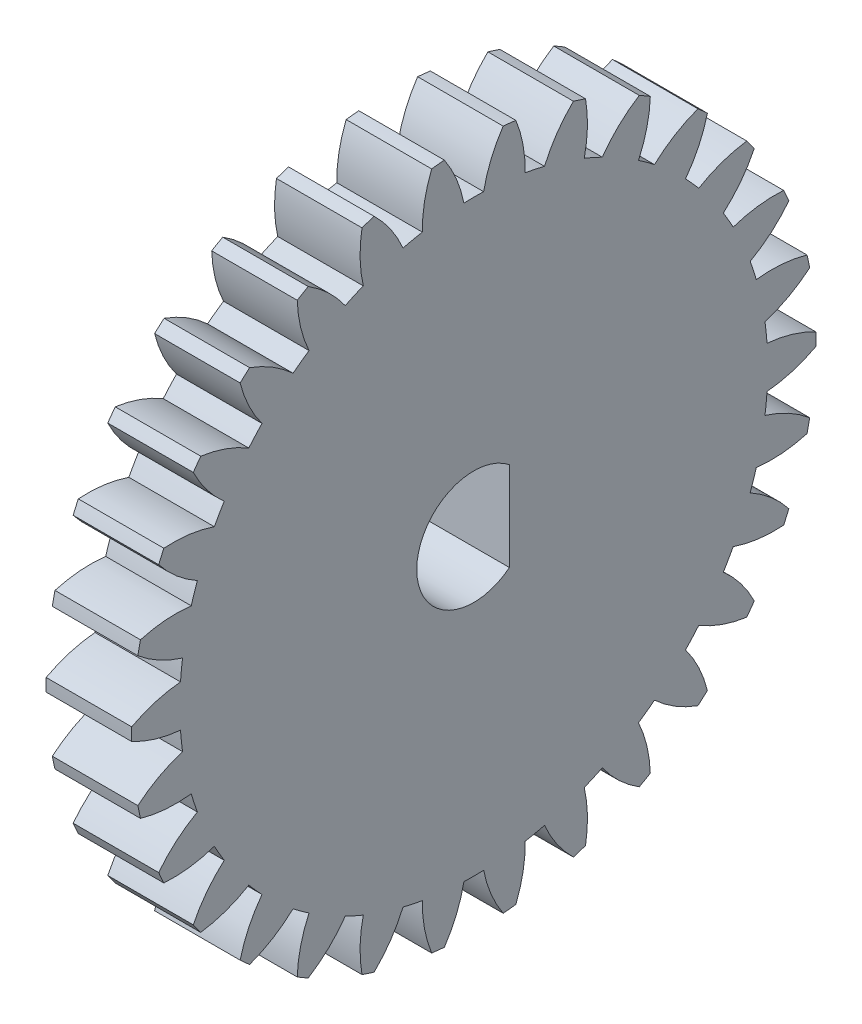
SolidWorks part; units mm, degrees
ref_plane "Plane1" through (0, 0, 0) normal (0, 0, 1) x (1, 0, 0)
ref_plane "Plane2" through (0, 0, 0) normal (0, 1, 0) x (1, 0, 0)
ref_plane "Plane3" through (0, 0, 0) normal (1, 0, 0) x (0, 0, -1)
sketch "HoldingSke" plane through (0, 0, 0) normal (0, 1, 0) x (1, 0, 0)
  line L0 (0, 0) -> (0.5774, -0.3333)
  line L1 (-15, 0) -> (100, 0) construction
  line L2 (0, 0) -> (-2.1039, 2.3779)
  line L3 (0, 0) -> (-11.863, 4.5341)
  line L4 (0, 0) -> (7.479, 4.318)
  line L5 (0, 0) -> (-46.8476, -17.4728)
  line L6 (0, 0) -> (-9.9476, -6.7116)
  line L7 (-2.1039, 2.3779) -> (8.6586, 51.2059)
  line L8 (-76.2, 54.61) -> (-76.1, 54.61)
  line L9 (-71.009, 38.7566) -> (-53.1078, 45.2721)
  line L10 (-76.2, 71.12) -> (104.1128, 71.12)
  line L11 (0, 0) -> (-12, 0)
  line L12 (-76.2, 101.6) -> (-76.147, 101.6)
  line L13 (24.9733, 27.94) -> (52.9518, 28.4284)
  line L14 (24.9733, 27.94) -> (24.9743, 27.94)
  line L15 (24.9733, 27.94) -> (100.4006, 29.5858)
  line L16 (-63.627, -1.5) -> (-12.827, -1.5)
  circle A0 centre (0, 0) radius 0.4
  circle A1 centre (0, 0) radius 20.624
  circle A2 centre (0, 0) radius 37.5
  circle A3 centre (0, 0) radius 0.4
  dimension "MHD" = 41.248
  dimension "Hub_dia" = 75
  dimension "Bore" = 0.8
  dimension "MBD" = 0.8
  dimension "Num_teeth" = 30
  dimension "Pitch_radius" = 180.3128
  dimension "Pitch" = 0.6667
  dimension "Width" = 12
  dimension "Overall_len" = 50
  dimension "Show_teeth" = 30
  dimension "Thickness" = 12
  dimension "OAL" = 50.0001
  dimension "T_dim" = 0.1
  dimension "Ap" = 20
  dimension "H" = 19.05
  dimension "Backlash" = 0.053
  dimension "Addendum_fac" = 1
  dimension "Dedendum_fac" = 1.25
  dimension "Clearance_fac" = 0.25
  dimension "Dedendum_add" = 0.001
  dimension "Module" = 1.5
sketch "BasProSke" plane through (0, 0, 0) normal (0, 1, 0) x (1, 0, 0)
  line L0 (-10, 0) -> (60, 0) construction
  line L1 (0, 0) -> (0, 24)
  line L2 (0, 0) -> (12, 0)
  line L3 (12, 0) -> (12, 24)
  line L4 (12, 24) -> (0, 24)
  dimension "Diameter" = 48
  dimension "Thickness" = 12
revolve "Base-Revolve" add sketch "BasProSke" angle 360 about L0
sketch "TooCutSke" plane through (0, 0, 0) normal (1, 0, 0) x (0, 0, -1)
  line L1 (0, 0) -> (0, 107) construction
  line L2 (0, 0) -> (-1.2703, 22.4641) construction
  line L3 (0, 0) -> (-4.6983, 44.7014) construction
  line L4 (-1.2703, 22.4641) -> (-2.3492, 22.3507) construction
  arc A0 (0.6933, 20.6123) -> (-0.6933, 20.6123) centre (0, 0) ccw
  arc A1 (2.0805, 23.9351) -> (-2.0805, 23.9351) centre (0, 0) ccw
  circle A2 centre (0, 0) radius 22.5 construction
  circle A3 centre (0, 0) radius 21.1431 construction
  arc A4 (-0.6933, 20.6123) -> (-2.0805, 23.9351) centre (-9.5243, 18.8764) ccw
  arc A5 (2.0805, 23.9351) -> (0.6933, 20.6123) centre (9.5243, 18.8764) ccw
  dimension "Root_dia" = 41.248
  dimension "Overcut_dia" = 48.0508
  dimension "Pitch_dia" = 45
  dimension "Base_dia" = 42.2862
  dimension "Flank_rad" = 9
  dimension "Half_ang" = 6
  dimension "Half_CT" = 1.0848
extrude "ToothCut" cut sketch "TooCutSke" along normal through all
fillet "Breaks" [suppressed] radius 0.03
fillet "RootFillets" [suppressed] radius 0.376
pattern_circular "TeethCuts" count 30 every 12 about axis through (-10, 0, 0) along (1, 0, 0) of "ToothCut", "RootFillets", "Breaks"
sketch "HubNeaOneSke" plane through (0, 0, 0) normal (-1, 0, 0) x (0, 0, 1)
  circle A0 centre (0, 0) radius 20.624
  dimension "Diameter" = 41.248
extrude "HubNearOne" [suppressed] add sketch "HubNeaOneSke" along normal blind 38.0001
sketch "HubNeaBotSke" plane through (0, 0, 0) normal (-1, 0, 0) x (0, 0, 1)
  circle A0 centre (0, 0) radius 20.624
  dimension "Diameter" = 41.248
extrude "HubNearBoth" [suppressed] add sketch "HubNeaBotSke" along normal blind 19
ref_plane "FarPln" through (12, 0, 0) normal (1, 0, 0) x (0, 0, -1)
sketch "HubFarSke" plane through (12, 0, 0) normal (1, 0, 0) x (0, 0, -1)
  circle A0 centre (0, 0) radius 20.624
  dimension "Diameter" = 41.248
extrude "HubFar" [suppressed] add sketch "HubFarSke" along normal blind 19
sketch "BorSke" plane through (0, 0, 0) normal (1, 0, 0) x (0, 0, -1)
  circle A0 centre (0, 0) radius 0.4
  dimension "Diameter" = 0.8
extrude "Bore" cut sketch "BorSke" along normal mid plane 100.0001
sketch "KeySke" plane through (0, 0, 0) normal (1, 0, 0) x (0, 0, -1)
  line L0 (-0.05, 0) -> (-0.05, 0.5)
  line L1 (-0.05, 0.5) -> (0.05, 0.5)
  line L2 (0.05, 0.5) -> (0.05, 0)
  line L3 (0, 0) -> (0, 34) construction
  line L4 (-0.05, 0) -> (0.05, 0)
  dimension "Offset" = 0.5
  dimension "Width" = 0.1
extrude "Keyway" [suppressed] cut sketch "KeySke" along normal mid plane 100.0001
pattern_circular "Keyway2" [suppressed] count 2 every 90 about axis through (-10, 0, 0) along (1, 0, 0)
sketch "Sketch1" plane through (0, 0, 0) normal (-1, 0, 0) x (0, 0, 1)
  circle A0 centre (-0.4, 0) radius 33.8416
  circle A1 centre (0, 0) radius 0.4 construction
extrude "Cut-Extrude1" cut sketch "Sketch1" against normal offset from surface (6 mm away) 6 up to face at (12, 0, 0)
sketch "Sketch2" plane through (6, 0, 0) normal (-1, 0, 0) x (0, 0, 1)
  line L0 (-2.5, 3.1225) -> (-2.5, -3.1225)
  circle A0 centre (0, 0) radius 4
  dimension "D1" = 8
  dimension "D2" = 2.5
extrude "Cut-Extrude2" cut sketch "Sketch2" against normal blind 6 contours L0 A0
equation "' \"Module@HoldingSke\" = 6.35"
equation "' \"Num_teeth@HoldingSke\" = 12"
equation "' \"Ap@HoldingSke\" =  20"
equation "' \"Width@HoldingSke\" = 0.5 * 25.4"
equation "' \"Hub_dia@HoldingSke\"= 1 * 25.4"
equation "' \"Overall_len@HoldingSke\" = 1.0 * 25.4"
equation "' \"Bore@HoldingSke\" = 0.75 * 25.4"
equation "' \"T_dim@HoldingSke\" = 0.1 * 25.4"
equation "' \"Width@KeySke\" = 0.25 * 25.4"
equation "' \"Show_teeth@HoldingSke\" = 13"
equation "' \"Backlash@HoldingSke\" = 0.009 * 25.4"
equation "' \"Addendum_fac@HoldingSke\" = 1.0"
equation "' \"Dedendum_fac@HoldingSke\" = 1.25"
equation "' \"Dedendum_add@HoldingSke\" = 0.00005 * 25.4"
equation "' \"Clearance_fac@HoldingSke\" = 0.25"
equation "\"Pitch@HoldingSke\" = 1 / \"Module@HoldingSke\""
equation "\"Overcut_dia@TooCutSke\" = (\"Num_teeth@HoldingSke\" + 2 * \"Addendum_fac@HoldingSke\") / \"Pitch@HoldingSke\" + 0.002 * 25.4"
equation "\"Pitch_dia@TooCutSke\" = \"Num_teeth@HoldingSke\" / \"Pitch@HoldingSke\""
equation "\"Base_dia@TooCutSke\" = \"Num_teeth@HoldingSke\" / \"Pitch@HoldingSke\" * cos((\"Ap@HoldingSke\"  * 3.14159265 / 180))"
equation "\"Root_dia@TooCutSke\" = (\"Num_teeth@HoldingSke\" + 2) / \"Pitch@HoldingSke\" - 2 * (\"Addendum_fac@HoldingSke\" + \"Dedendum_fac@HoldingSke\") / \"Pitch@HoldingSke\" - \"Dedendum_add@HoldingSke\" * 2"
equation "\"Half_ang@TooCutSke\" = 180 / \"Num_teeth@HoldingSke\""
equation "\"Half_CT@TooCutSke\" = \"Num_teeth@HoldingSke\" / \"Pitch@HoldingSke\" * sin((3.14159265 / 2 / \"Num_teeth@HoldingSke\")) / 2 - 7 * \"Backlash@HoldingSke\" / 4"
equation "\"Flank_rad@TooCutSke\" = \"Num_teeth@HoldingSke\" / \"Pitch@HoldingSke\" / 5"
equation "\"Radius@RootFillets\" = \"Clearance_fac@HoldingSke\" / \"Pitch@HoldingSke\" + \"Dedendum_add@HoldingSke\""
equation "\"Break_rad@Breaks\" = 0.02 / \"Pitch@HoldingSke\""
equation "\"Thickness@HoldingSke\" = \"Width@HoldingSke\""
equation "\"OAL@HoldingSke\" = \"Thickness@HoldingSke\""
equation "\"MHD@HoldingSke\" = (\"Num_teeth@HoldingSke\" + 2) / \"Pitch@HoldingSke\" - 2 * (\"Addendum_fac@HoldingSke\" + \"Dedendum_fac@HoldingSke\")  / \"Pitch@HoldingSke\" - \"Dedendum_add@HoldingSke\" * 2"
equation "\"MBD@HoldingSke\" = (\"Num_teeth@HoldingSke\" + 2) / \"Pitch@HoldingSke\" - 2 * (\"Addendum_fac@HoldingSke\" + \"Dedendum_fac@HoldingSke\")  / \"Pitch@HoldingSke\" - \"Dedendum_add@HoldingSke\" * 2 - 0.002 * 25.4"
equation "\"MHD@HoldingSke\" = ((sgn( \"MHD@HoldingSke\" - \"Hub_dia@HoldingSke\" )-1)*( \"MHD@HoldingSke\" - \"Hub_dia@HoldingSke\" ))/-2+ \"Hub_dia@HoldingSke\""
equation "\"MBD@HoldingSke\" = ((sgn( \"MBD@HoldingSke\" - \"Bore@HoldingSke\" )-1)*( \"MBD@HoldingSke\" - \"Bore@HoldingSke\" ))/-2+ \"Bore@HoldingSke\""
equation "\"OAL@HoldingSke\" = ((sgn( \"OAL@HoldingSke\" - \"Overall_len@HoldingSke\" )+1)*( \"OAL@HoldingSke\" - \"Overall_len@HoldingSke\" ))/2 + \"Overall_len@HoldingSke\" + 0.000002 * 25.4"
equation "\"Num_teeth@TeethCuts\" = int( \"Show_teeth@HoldingSke\" ) + 1"
equation "\"Num_teeth@TeethCuts\" = ((sgn( \"Num_teeth@TeethCuts\" - \"Num_teeth@HoldingSke\" )-1)*( \"Num_teeth@TeethCuts\" - \"Num_teeth@HoldingSke\" ))/-2+ \"Num_teeth@HoldingSke\""
equation "\"Num_teeth@TeethCuts\" = ((sgn( \"Num_teeth@TeethCuts\" - 2.0)+1)*( \"Num_teeth@TeethCuts\" - 2.0))/2 +2.0"
equation "\"Angle@TeethCuts\" = 360.0 / \"Num_teeth@HoldingSke\""
equation "\"Diameter@BasProSke\" = (\"Num_teeth@HoldingSke\" + 2 * \"Addendum_fac@HoldingSke\") / \"Pitch@HoldingSke\""
equation "\"Thickness@BasProSke\"  = \"Thickness@HoldingSke\""
equation "' \"Fillet_rad@BasProSke\" =  \"Thickness@HoldingSke\" * 0.05"
equation "\"MHD@HoldingSke\" = ((sgn( \"MHD@HoldingSke\" - \"Root_dia@TooCutSke\" )-1)*( \"MHD@HoldingSke\" - \"Root_dia@TooCutSke\" ))/-2+ \"Root_dia@TooCutSke\""
equation "\"Diameter@HubNeaOneSke\" = \"MHD@HoldingSke\""
equation "\"Length@HubNearOne\" = \"OAL@HoldingSke\" - \"Thickness@BasProSke\""
equation "\"Diameter@HubNeaBotSke\" = \"MHD@HoldingSke\""
equation "\"Length@HubNearBoth\" = ( \"OAL@HoldingSke\" - \"Thickness@BasProSke\" ) / 2.0"
equation "\"Thickness@FarPln\" = \"Thickness@BasProSke\""
equation "\"Diameter@HubFarSke\" = \"MHD@HoldingSke\""
equation "\"Length@HubFar\" = ( \"OAL@HoldingSke\" - \"Thickness@BasProSke\" ) / 2.0"
equation "\"Diameter@BorSke\" = \"MBD@HoldingSke\""
equation "\"D1@Bore\" = \"OAL@HoldingSke\" * 2.0"
equation "\"D1@Keyway\" = \"OAL@HoldingSke\" * 2.0"
equation "\"Offset@KeySke\" = \"T_dim@HoldingSke\" + \"MBD@HoldingSke\" / 2.0"
